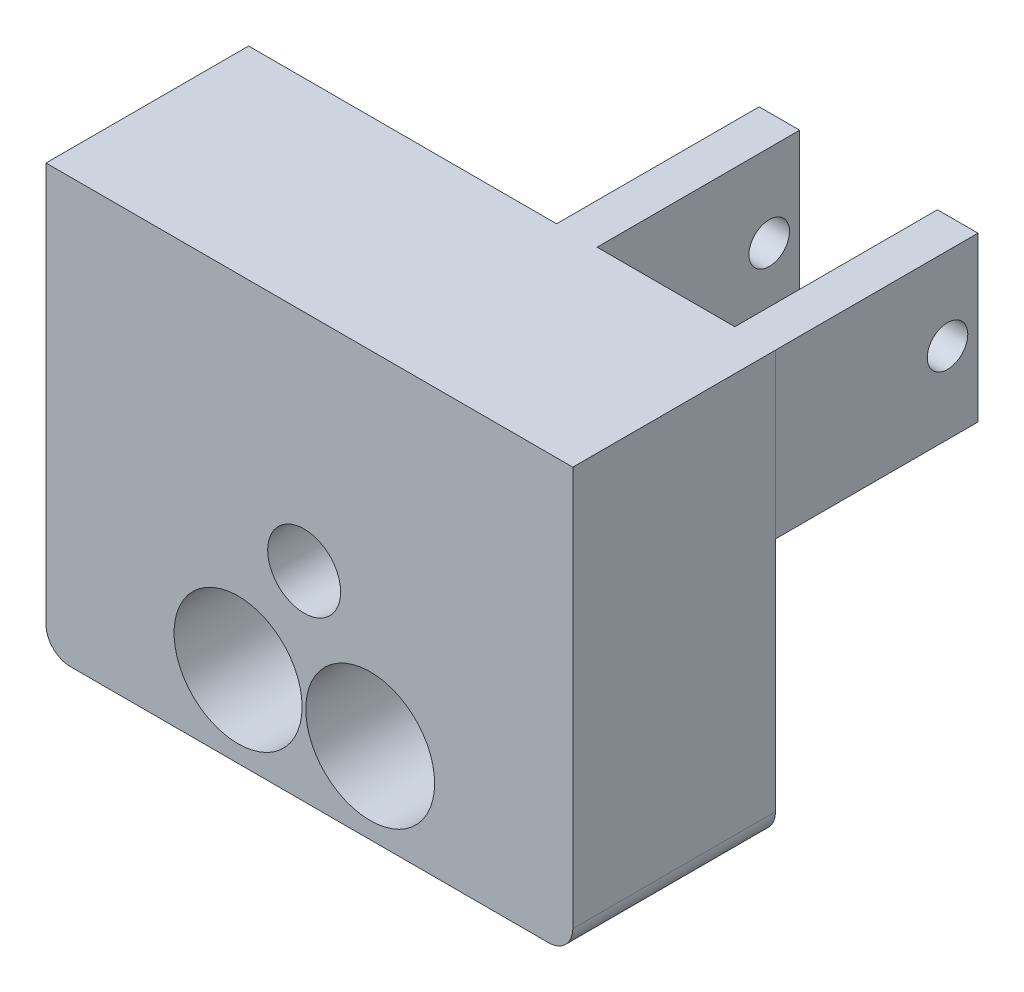
SolidWorks part; units mm, degrees
ref_plane "Plan de face" through (0, 0, 0) normal (0, 0, 1) x (1, 0, 0)
ref_plane "Plan de dessus" through (0, 0, 0) normal (0, 1, 0) x (1, 0, 0)
ref_plane "Plan de droite" through (0, 0, 0) normal (1, 0, 0) x (0, 0, -1)
sketch "Esquisse1" plane through (0, 0, 0) normal (0, 0, 1) x (1, 0, 0)
  line L1 (0, 0) -> (105, 0)
  line L2 (0, 0) -> (0, 80)
  line L3 (0, 80) -> (105, 80)
  line L4 (105, 0) -> (105, 80)
  dimension "D1" = 80
  dimension "D2" = 105
extrude "Boss.-Extru.1" add sketch "Esquisse1" along normal blind 25
sketch "Esquisse2" plane through (0, 0, 0) normal (0, 0, 1) x (1, 0, 0)
  line L0 (0, 0) -> (105, 0) construction
  line L1 (105, 0) -> (105, 80) construction
  line L2 (0, 0) -> (105, 0) construction
  circle A0 centre (63.7, 10) radius 7.9
  circle A1 centre (80, 10) radius 7.95
  circle A2 centre (71.85, 24.6335) radius 4.5
  dimension "D1" = 9
  dimension "D2" = 15.9
  dimension "D3" = 15.8
  dimension "D12" = 10
  dimension "D4" = 16.3
  dimension "D5" = 16.75
  dimension "D6" = 16.75
  dimension "D7" = 10
  dimension "D8" = 25
extrude "Enlèv. mat.-Extru.1" cut sketch "Esquisse2" along normal through all
sketch "Esquisse3" plane through (0, 0, 0) normal (0, 1, 0) x (1, 0, 0)
  line L1 (105, -25) -> (105, 0) construction
  line L2 (0, 0) -> (105, 0) construction
  circle A0 centre (49, -12.5) radius 4
  circle A1 centre (93, -12.5) radius 4
  dimension "D1" = 8
  dimension "D2" = 8
  dimension "D4" = 12
  dimension "D6" = 12.5
  dimension "D3" = 44
  dimension "D5" = 12.5
extrude "Enlèv. mat.-Extru.3" cut sketch "Esquisse3" along normal blind 10
sketch "Esquisse6" plane through (0, 0, 0) normal (0, 0, 1) x (1, 0, 0)
  line L0 (0, 0) -> (105, 0) construction
  line L1 (40, 0) -> (0, 0)
  line L2 (40, 0) -> (40, 80)
  line L3 (40, 80) -> (0, 80)
  line L4 (0, 0) -> (0, 80)
  dimension "D1" = 40
extrude "Enlèv. mat.-Extru.6" cut sketch "Esquisse6" along normal through all
sketch "Esquisse7" plane through (0, 0, 0) normal (0, 0, 1) x (1, 0, 0)
  line L0 (40, 0) -> (40, 80) construction
  line L1 (105, 80) -> (40, 80)
  line L2 (105, 80) -> (105, 77.3119)
  line L3 (105, 77.3119) -> (40, 77.3119)
  line L4 (40, 80) -> (40, 77.3119)
extrude "Enlèv. mat.-Extru.7" cut sketch "Esquisse7" along normal through all
fillet "Congé1" radius 3 4 edges at (105, 77.3119, 12.5) (40, 77.3119, 12.5) (40, 0, 12.5) (105, 0, 12.5)
sketch "Esquisse9" plane through (0, 0, 0) normal (0, 0, 1) x (1, 0, 0)
  line L0 (43, 77.3119) -> (102, 77.3119) construction
  line L1 (104.9917, 32.1324) -> (99.9917, 32.1324)
  line L2 (104.9917, 32.1324) -> (104.9917, 52.3119)
  line L3 (104.9917, 52.3119) -> (99.9917, 52.3119)
  line L4 (99.9917, 32.1324) -> (99.9917, 52.3119)
  line L5 (82.9917, 52.3119) -> (77.9917, 52.3119)
  line L6 (82.9917, 52.3119) -> (82.9917, 32.1319)
  line L7 (82.9917, 32.1319) -> (77.9917, 32.1319)
  line L8 (77.9917, 52.3119) -> (77.9917, 32.1319)
  point P8 (102.4917, 52.3119)
  point P11 (80.4917, 52.3119)
  dimension "D1" = 17
  dimension "D2" = 2.5
  dimension "D3" = 5
  dimension "D4" = 20.1794
  dimension "D5" = 25
  dimension "D6" = 25
  dimension "D7" = 20.18
extrude "Boss.-Extru.2" add sketch "Esquisse9" against normal blind 25
sketch "Esquisse10" plane through (104.9917, 0, 0) normal (1, 0, 0) x (0, 0, -1)
  line L0 (0, 32.1324) -> (0, 52.3119) construction
  line L1 (25, 32.1324) -> (0, 32.1324) construction
  circle A0 centre (21.24, 42.1324) radius 2.5
  point P5 (0, 42.2222)
  dimension "D1" = 5
  dimension "D2" = 21.24
  dimension "D3" = 10
extrude "Enlèv. mat.-Extru.8" cut sketch "Esquisse10" against normal through all
sketch "Esquisse11" plane through (0, 0, 0) normal (0, 0, -1) x (-1, 0, 0)
  line L1 (-73.3817, 32.158) -> (-79.1322, 27.0693)
  line L2 (-79.1322, 27.0693) -> (-77.6005, 19.5448)
  line L3 (-77.6005, 19.5448) -> (-70.3183, 17.1091)
  line L4 (-70.3183, 17.1091) -> (-64.5678, 22.1978)
  line L5 (-64.5678, 22.1978) -> (-66.0995, 29.7222)
  line L6 (-66.0995, 29.7222) -> (-73.3817, 32.158)
  circle A0 centre (-71.85, 24.6335) radius 6.65 construction
  dimension "D1" = 13.3
extrude "Enlèv. mat.-Extru.9" cut sketch "Esquisse11" against normal blind 7.5
sketch "Esquisse12" plane through (0, 0, 0) normal (0, 0, -1) x (-1, 0, 0)
  line L0 (-105.676, 77.3306) -> (-105.676, 52.3119)
  line L1 (-104.9917, 52.3119) -> (-39.9853, 52.3119)
  line L2 (-105.676, 52.3119) -> (-104.9917, 52.3119)
  line L3 (-104.9917, 77.3306) -> (-39.9853, 77.3306)
  line L4 (-39.9853, 52.3119) -> (-39.9853, 77.3306)
  line L5 (-104.9917, 77.3306) -> (-105.676, 77.3306)
extrude "Enlèv. mat.-Extru.11" cut sketch "Esquisse12" against normal through all
sketch "Esquisse13" plane through (40, 0, 0) normal (-1, 0, 0) x (0, 0, 1)
  circle A0 centre (15, 14.7519) radius 1.5
  circle A1 centre (15, 26) radius 1.5
  dimension "D1" = 3
  dimension "D2" = 3
extrude "Enlèv. mat.-Extru.12" cut sketch "Esquisse13" against normal blind 3
